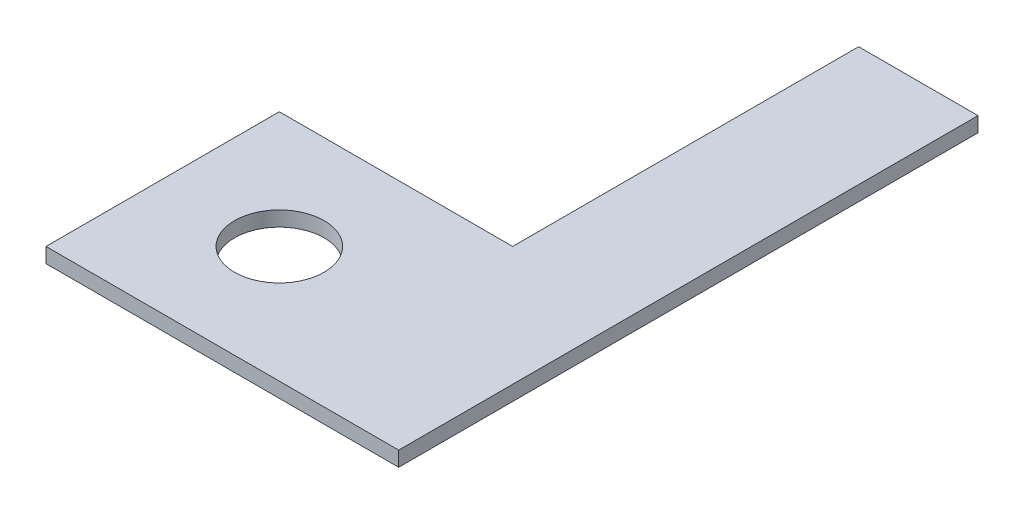
SolidWorks part; units mm, degrees
ref_plane "Front Plane" through (0, 0, 0) normal (0, 0, 1) x (1, 0, 0)
ref_plane "Top Plane" through (0, 0, 0) normal (0, 1, 0) x (1, 0, 0)
ref_plane "Right Plane" through (0, 0, 0) normal (1, 0, 0) x (0, 0, -1)
sketch "Sketch1" plane through (0, 0, 0) normal (0, 1, 0) x (1, 0, 0)
  line L1 (-31.635, 31.635) -> (31.635, 31.635)
  line L2 (-31.635, 31.635) -> (-31.635, -31.635)
  line L3 (-31.635, -31.635) -> (31.635, -31.635)
  line L4 (31.635, 31.635) -> (31.635, -31.635)
  line L5 (-31.635, 31.635) -> (31.635, -31.635) construction
  line L6 (-31.635, -31.635) -> (31.635, 31.635) construction
  dimension "D1" = 63.27
  dimension "D2" = 63.27
extrude "Boss-Extrude1" add sketch "Sketch1" along normal blind 2
sketch "Sketch2" plane through (0, 2, 0) normal (0, 1, 0) x (1, 0, 0)
  circle A0 centre (0, 0) radius 6
extrude "Cut-Extrude1" cut sketch "Sketch2" against normal blind 2
sketch "Sketch3" plane through (0, 2, 0) normal (0, 1, 0) x (1, 0, 0)
  line L1 (15.635, 0) -> (31.635, 0)
  line L2 (15.635, 0) -> (15.635, 62)
  line L3 (15.635, 62) -> (31.635, 62)
  line L4 (31.635, 0) -> (31.635, 62)
  line L5 (31.635, -31.635) -> (31.635, 31.635) construction
  point P4 (0, 0)
  point P5 (0, 0)
  point P6 (0, 0)
  dimension "D1" = 62
  dimension "D2" = 16
extrude "Boss-Extrude2" add sketch "Sketch3" against normal blind 2
sketch "Sketch4" plane through (0, 0, 0) normal (0, -1, 0) x (1, 0, 0)
  line L0 (-31.635, 31.635) -> (31.635, 31.635) construction
  line L1 (-31.635, -31.635) -> (-15.635, -31.635)
  line L2 (-31.635, -31.635) -> (-31.635, 31.635)
  line L3 (-31.635, 31.635) -> (-15.635, 31.635)
  line L4 (-15.635, -31.635) -> (-15.635, 31.635)
  dimension "D1" = 16
extrude "Cut-Extrude2" cut sketch "Sketch4" against normal blind 10
sketch "Sketch5" plane through (0, 0, 0) normal (0, -1, 0) x (1, 0, 0)
  line L0 (-15.635, 31.635) -> (31.635, 31.635) construction
  line L1 (-15.635, 31.635) -> (31.635, 31.635)
  line L2 (-15.635, 31.635) -> (-15.635, 15.635)
  line L3 (-15.635, 15.635) -> (31.635, 15.635)
  line L4 (31.635, 31.635) -> (31.635, 15.635)
  line L5 (-15.635, -31.635) -> (-15.635, 31.635) construction
  line L6 (31.635, 31.635) -> (31.635, -62) construction
  dimension "D1" = 16
extrude "Cut-Extrude3" cut sketch "Sketch5" against normal blind 10
sketch "Sketch6" plane through (0, 0, 0) normal (0, -1, 0) x (1, 0, 0)
  line L1 (-15.635, -31.635) -> (15.635, -31.635)
  line L2 (-15.635, -31.635) -> (-15.635, -15.635)
  line L3 (-15.635, -15.635) -> (15.635, -15.635)
  line L4 (15.635, -31.635) -> (15.635, -15.635)
  dimension "D1" = 16
  dimension "D2" = 31.27
extrude "Cut-Extrude4" cut sketch "Sketch6" against normal blind 10
